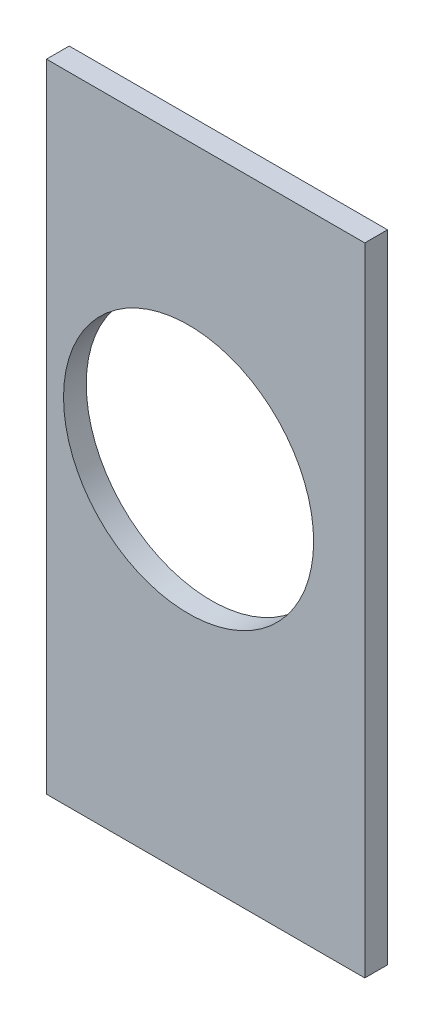
SolidWorks part; units mm, degrees
ref_plane "Plan de face" through (0, 0, 0) normal (0, 0, 1) x (1, 0, 0)
ref_plane "Plan de dessus" through (0, 0, 0) normal (0, 1, 0) x (1, 0, 0)
ref_plane "Plan de droite" through (0, 0, 0) normal (1, 0, 0) x (0, 0, -1)
sketch "Esquisse1" plane through (0, 0, 0) normal (0, 0, 1) x (1, 0, 0)
  line L1 (0, 0) -> (140, 0)
  line L2 (0, 0) -> (0, 280)
  line L3 (0, 280) -> (140, 280)
  line L4 (140, 0) -> (140, 280)
  dimension "D1" = 280
  dimension "D2" = 140
extrude "Boss.-Extru.1" add sketch "Esquisse1" along normal blind 10
sketch "Esquisse2" plane through (0, 0, 10) normal (0, 0, 1) x (1, 0, 0)
  line L0 (62.5, 0) -> (62.5, 155) construction
  line L2 (0, 0) -> (140, 0) construction
  line L4 (140, 0) -> (140, 280) construction
  circle A0 centre (62.5, 155) radius 55
  dimension "D1" = 110
  dimension "D2" = 155
  dimension "D3" = 77.5
extrude "Enlèv. mat.-Extru.1" cut sketch "Esquisse2" against normal through all both and the other way through all
